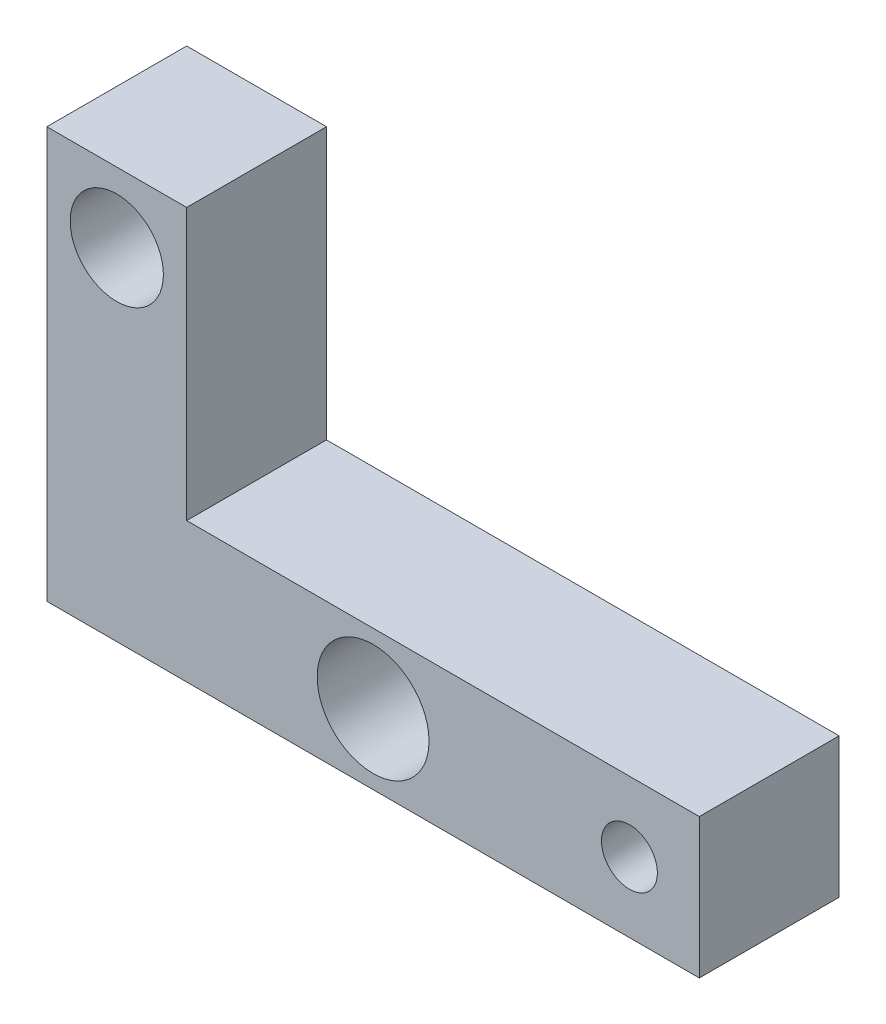
SolidWorks part; units mm, degrees
ref_plane "前基準面" through (0, 0, 0) normal (0, 0, 1) x (1, 0, 0)
ref_plane "上基準面" through (0, 0, 0) normal (0, 1, 0) x (1, 0, 0)
ref_plane "右基準面" through (0, 0, 0) normal (1, 0, 0) x (0, 0, -1)
sketch "草圖1" plane through (0, 0, 0) normal (0, 0, 1) x (1, 0, 0)
  line L0 (0, 0) -> (0, 44.0962)
  line L1 (0, 44.0962) -> (15, 44.0962)
  line L2 (15, 44.0962) -> (15, 15)
  line L3 (15, 15) -> (70, 15)
  line L4 (70, 15) -> (70, 0)
  line L5 (70, 0) -> (0, 0)
  circle A0 centre (7.5, 36.5962) radius 5
  circle A1 centre (62.5, 7.5) radius 3
  circle A2 centre (35, 7.5) radius 6
  dimension "D4" = 10
  dimension "D5" = 12
  dimension "D6" = 6
  dimension "D7" = 7.5
  dimension "D8" = 7.5
  dimension "D9" = 7.5
  dimension "D10" = 35
  dimension "D11" = 7.5
  dimension "D12" = 7.5
  dimension "D1" = 70
  dimension "D2" = 15
  dimension "D3" = 15
extrude "填料-伸長1" add sketch "草圖1" along normal blind 15
